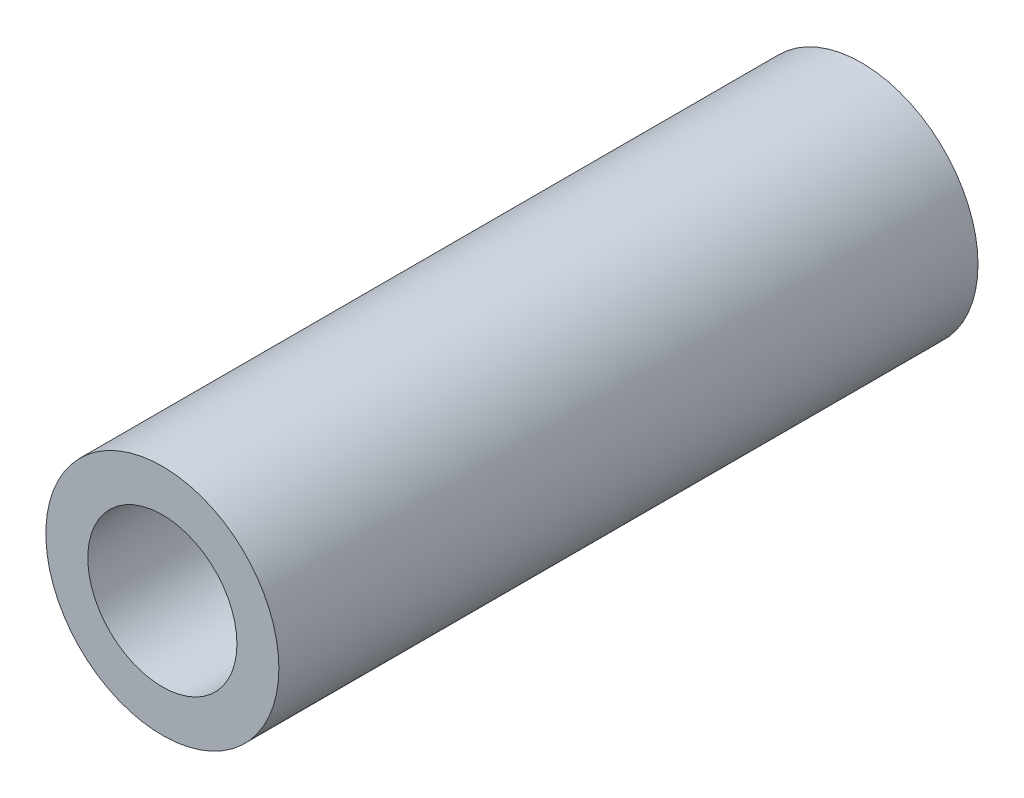
SolidWorks part; units mm, degrees
ref_plane "正面" through (0, 0, 0) normal (0, 0, 1) x (1, 0, 0)
ref_plane "平面" through (0, 0, 0) normal (0, 1, 0) x (1, 0, 0)
ref_plane "右側面" through (0, 0, 0) normal (1, 0, 0) x (0, 0, -1)
sketch "ｽｹｯﾁ1" plane through (0, 0, 0) normal (0, 0, 1) x (1, 0, 0)
  circle A0 centre (0, 0) radius 1.6
  circle A1 centre (0, 0) radius 2.5
  dimension "D1" = 5
  dimension "D2" = 3.2
extrude "ﾎﾞｽ - 押し出し1" add sketch "ｽｹｯﾁ1" along normal blind 15
